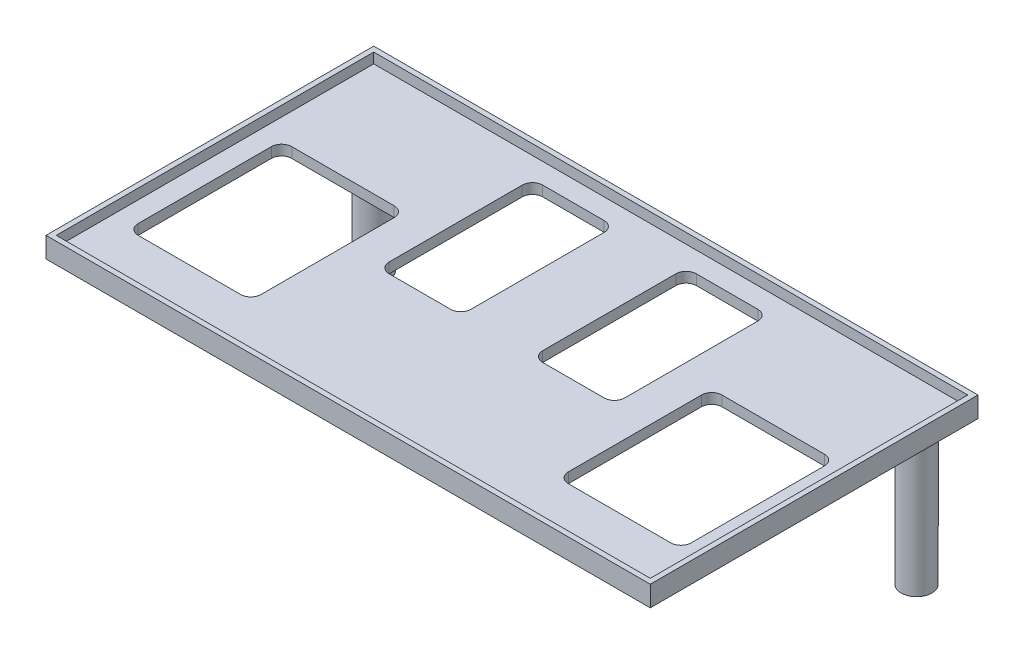
SolidWorks part; units mm, degrees
material "PVC hart"
ref_plane "Ebene vorne" through (0, 0, 0) normal (0, 0, 1) x (1, 0, 0)
ref_plane "Ebene oben" through (0, 0, 0) normal (0, 1, 0) x (1, 0, 0)
ref_plane "Ebene rechts" through (0, 0, 0) normal (1, 0, 0) x (0, 0, -1)
sketch "Skizze1" plane through (0, 0, 0) normal (0, 1, 0) x (1, 0, 0)
  line L1 (-29.5, 16) -> (29.5, 16)
  line L2 (-29.5, 16) -> (-29.5, -16)
  line L3 (-29.5, -16) -> (29.5, -16)
  line L4 (29.5, 16) -> (29.5, -16)
  line L5 (-29.5, 16) -> (29.5, -16) construction
  line L6 (-29.5, -16) -> (29.5, 16) construction
  point P0 (0, 0)
  dimension "D1" = 32
  dimension "D2" = 59
extrude "Aufsatz-Linear austragen1" add sketch "Skizze1" along normal blind 1
sketch "Skizze3" plane through (0, 1, 0) normal (0, 1, 0) x (1, 0, 0)
  line L14 (29, -15.5) -> (29, 15.5)
  line L15 (-29, -15.5) -> (29, -15.5)
  line L16 (-29, 15.5) -> (-29, -15.5)
  line L17 (29, 15.5) -> (-29, 15.5)
  line L18 (29, -15.5) -> (29, 15.5)
  line L19 (-29, -15.5) -> (29, -15.5)
  line L20 (-29, 15.5) -> (-29, -15.5)
  line L21 (29, 15.5) -> (-29, 15.5)
  line M13 (29.5, -16) -> (29.5, 16)
  line M14 (29.5, 16) -> (-29.5, 16)
  line M15 (-29.5, 16) -> (-29.5, -16)
  line M16 (-29.5, -16) -> (29.5, -16)
  dimension "D1" = 0.5
extrude "Aufsatz-Linear austragen2" add sketch "Skizze3" along normal blind 1 contours L21 L18 L19 L20 M16 M13 M14 M15
sketch "Skizze4" plane through (0, 0, 0) normal (0, -1, 0) x (1, 0, 0)
  line L0 (0, 20.7608) -> (0, -19.573) construction
  line L1 (-29.5, 16) -> (29.5, 16) construction
  circle A0 centre (8, 6) radius 1.55
  circle A1 centre (-8, 6) radius 1.55
  dimension "D1" = 3.1
  dimension "D2" = 10
  dimension "D3" = 16
extrude "Aufsatz-Linear austragen3" add sketch "Skizze4" along normal blind 1.5
sketch "Skizze5" plane through (0, 0, 0) normal (0, -1, 0) x (1, 0, 0)
  line L0 (-8, 6) -> (8, 6) construction
  line L1 (0, 18.925) -> (0, -20.2209) construction
  line L2 (29.5, -16) -> (-29.5, -16) construction
  line L3 (29.5, 16) -> (29.5, -16) construction
  circle A0 centre (26.5, -13) radius 1.5
  circle A1 centre (-26.5, -13) radius 1.5
  point P10 (25.7518, -12.0384)
  dimension "D1" = 3
  dimension "D2" = 3
  dimension "D3" = 3
extrude "Aufsatz-Linear austragen4" add sketch "Skizze5" along normal blind 14
fillet "Verrundung3" radius 1 2 edges at (-26.5, 0, -11.5) (26.5, 0, -11.5)
sketch "Skizze6" plane through (0, 0, 0) normal (0, -1, 0) x (1, 0, 0)
  line L0 (0, 22.1647) -> (0, -25.0804) construction
  line L1 (-29.5, 16) -> (29.5, 16) construction
  line L2 (16, 10.5) -> (26, 10.5)
  line L3 (15, 9.5) -> (15, -3.5)
  line L4 (16, -4.5) -> (26, -4.5)
  line L5 (27, 9.5) -> (27, -3.5)
  line L6 (15, 10.5) -> (27, -4.5) construction
  line L7 (15, -4.5) -> (27, 10.5) construction
  line L8 (4.5, 1.5) -> (10.5, 1.5)
  line L9 (3.5, 0.5) -> (3.5, -12.5)
  line L10 (4.5, -13.5) -> (10.5, -13.5)
  line L11 (11.5, 0.5) -> (11.5, -12.5)
  line L12 (3.5, 1.5) -> (11.5, -13.5) construction
  line L13 (3.5, -13.5) -> (11.5, 1.5) construction
  line L14 (29.5, -16) -> (-29.5, -16) construction
  line L15 (-3.5, -13.5) -> (-11.5, 1.5) construction
  line L16 (-3.5, 1.5) -> (-11.5, -13.5) construction
  line L21 (-15, -4.5) -> (-27, 10.5) construction
  line L22 (-15, 10.5) -> (-27, -4.5) construction
  line L27 (-11.5, 0.5) -> (-11.5, -12.5)
  line L28 (-4.5, -13.5) -> (-10.5, -13.5)
  line L29 (-3.5, 0.5) -> (-3.5, -12.5)
  line L30 (-4.5, 1.5) -> (-10.5, 1.5)
  line L31 (-27, 9.5) -> (-27, -3.5)
  line L32 (-16, -4.5) -> (-26, -4.5)
  line L33 (-15, 9.5) -> (-15, -3.5)
  line L34 (-16, 10.5) -> (-26, 10.5)
  arc A0 (10.5, -13.5) -> (11.5, -12.5) centre (10.5, -12.5) ccw
  arc A1 (3.5, -12.5) -> (4.5, -13.5) centre (4.5, -12.5) ccw
  arc A2 (4.5, 1.5) -> (3.5, 0.5) centre (4.5, 0.5) ccw
  arc A3 (10.5, 1.5) -> (11.5, 0.5) centre (10.5, 0.5) cw
  arc A4 (15, -3.5) -> (16, -4.5) centre (16, -3.5) ccw
  arc A5 (26, -4.5) -> (27, -3.5) centre (26, -3.5) ccw
  arc A6 (26, 10.5) -> (27, 9.5) centre (26, 9.5) cw
  arc A7 (16, 10.5) -> (15, 9.5) centre (16, 9.5) ccw
  arc A16 (-16, 10.5) -> (-15, 9.5) centre (-16, 9.5) cw
  arc A17 (-26, 10.5) -> (-27, 9.5) centre (-26, 9.5) ccw
  arc A18 (-26, -4.5) -> (-27, -3.5) centre (-26, -3.5) cw
  arc A19 (-15, -3.5) -> (-16, -4.5) centre (-16, -3.5) cw
  arc A20 (-10.5, 1.5) -> (-11.5, 0.5) centre (-10.5, 0.5) ccw
  arc A21 (-4.5, 1.5) -> (-3.5, 0.5) centre (-4.5, 0.5) cw
  arc A22 (-3.5, -12.5) -> (-4.5, -13.5) centre (-4.5, -12.5) cw
  arc A23 (-10.5, -13.5) -> (-11.5, -12.5) centre (-10.5, -12.5) cw
  point P3 (21, 3)
  point P8 (7.5, -6)
  point P13 (7.0193, -5.2105)
  point P14 (21.1658, 2.6727)
  point P15 (7.0193, -5.5344)
  point P76 (-7.5, -6)
  point P77 (-21, 3)
  dimension "D9" = 1
  dimension "D1" = 13
  dimension "D2" = 10
  dimension "D4" = 8
  dimension "D5" = 7.5
  dimension "D6" = 15
  dimension "D7" = 12
  dimension "D8" = 21
extrude "Schnitt-Linear austragen2" cut sketch "Skizze6" against normal up to surface (1 mm away) up to face at (0, 1, 0)
